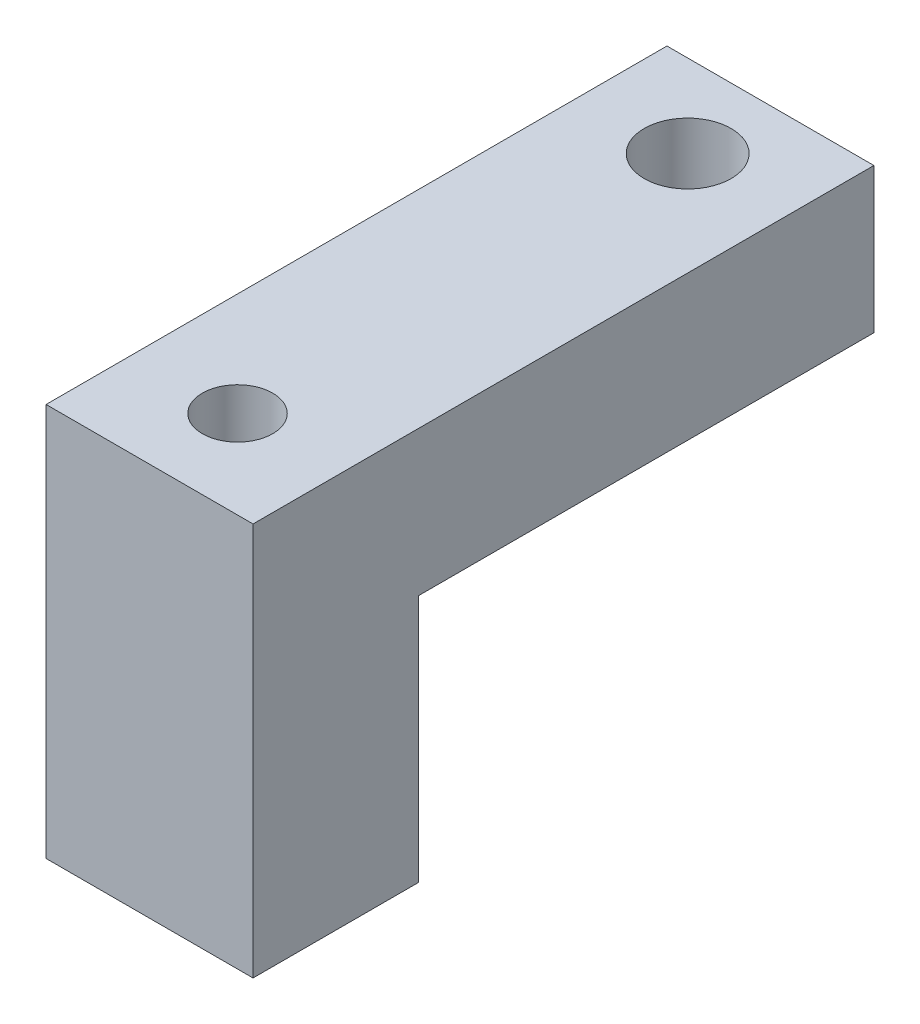
SolidWorks part; units mm, degrees
ref_plane "Front Plane" through (0, 0, 0) normal (0, 0, 1) x (1, 0, 0)
ref_plane "Top Plane" through (0, 0, 0) normal (0, 1, 0) x (1, 0, 0)
ref_plane "Right Plane" through (0, 0, 0) normal (1, 0, 0) x (0, 0, -1)
sketch "Sketch1" plane through (0, 0, 0) normal (0, 1, 0) x (1, 0, 0)
  line L1 (0, 0) -> (10, 0)
  line L2 (0, 0) -> (0, 30)
  line L3 (0, 30) -> (10, 30)
  line L4 (10, 0) -> (10, 30)
  circle A0 centre (5, 26) radius 2.1
  point P7 (5, 30)
  dimension "D3" = 4.2
  dimension "D4" = 4
  dimension "D1" = 10
  dimension "D2" = 30
extrude "Boss-Extrude1" add sketch "Sketch1" along normal blind 7
sketch "Sketch2" plane through (0, 0, 0) normal (0, -1, 0) x (-1, 0, 0)
  line L0 (-10, 0) -> (-10, 30) construction
  line L1 (0, 0) -> (-10, 0)
  line L2 (0, 0) -> (0, 8)
  line L3 (0, 8) -> (-10, 8)
  line L4 (-10, 0) -> (-10, 8)
  dimension "D1" = 8
extrude "Boss-Extrude2" add sketch "Sketch2" along normal blind 12
sketch "Sketch3" plane through (0, 7, 0) normal (0, 1, 0) x (1, 0, 0)
  line L0 (0, 0) -> (10, 0) construction
  circle A0 centre (5, 4.25) radius 1.7
  circle A1 centre (5, 26) radius 2.1 construction
  point P4 (5, 0)
  dimension "D1" = 3.4
  dimension "the_length" = 21.75
extrude "Cut-Extrude1" cut sketch "Sketch3" against normal through all
